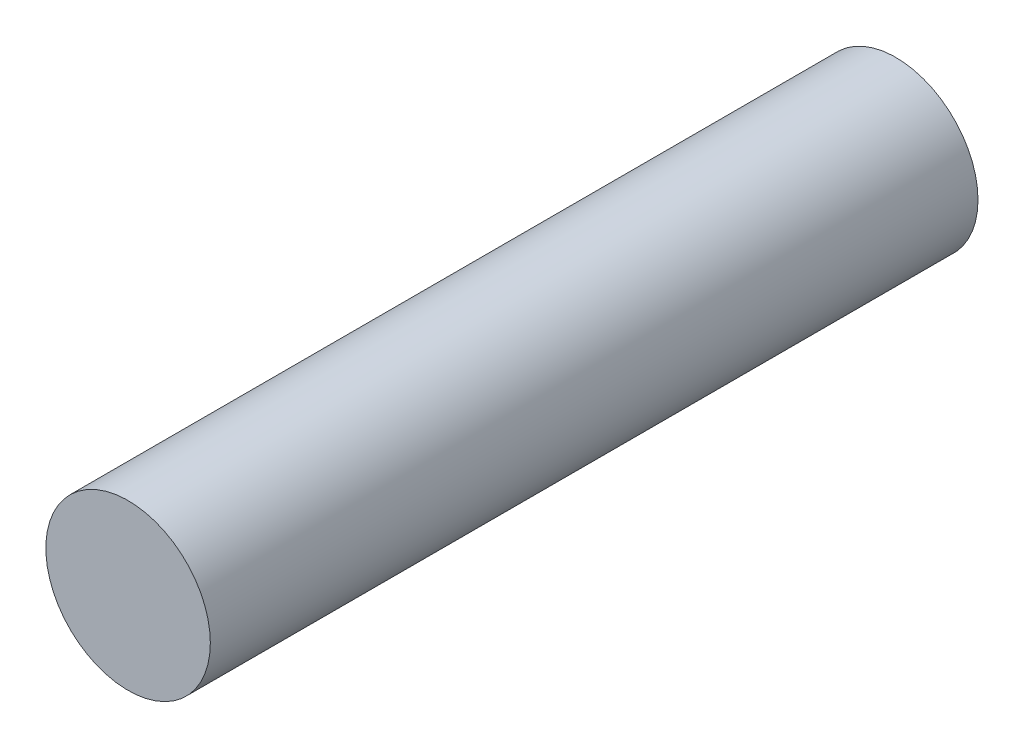
SolidWorks part; units mm, degrees
ref_plane "Front Plane" through (0, 0, 0) normal (0, 0, 1) x (1, 0, 0)
ref_plane "Top Plane" through (0, 0, 0) normal (0, 1, 0) x (1, 0, 0)
ref_plane "Right Plane" through (0, 0, 0) normal (1, 0, 0) x (0, 0, -1)
sketch "Sketch1" plane through (0, 0, 0) normal (0, 0, 1) x (1, 0, 0)
  circle A0 centre (0, 0) radius 7.5
  dimension "D1" = 15
extrude "Boss-Extrude1" add sketch "Sketch1" along normal blind 70
